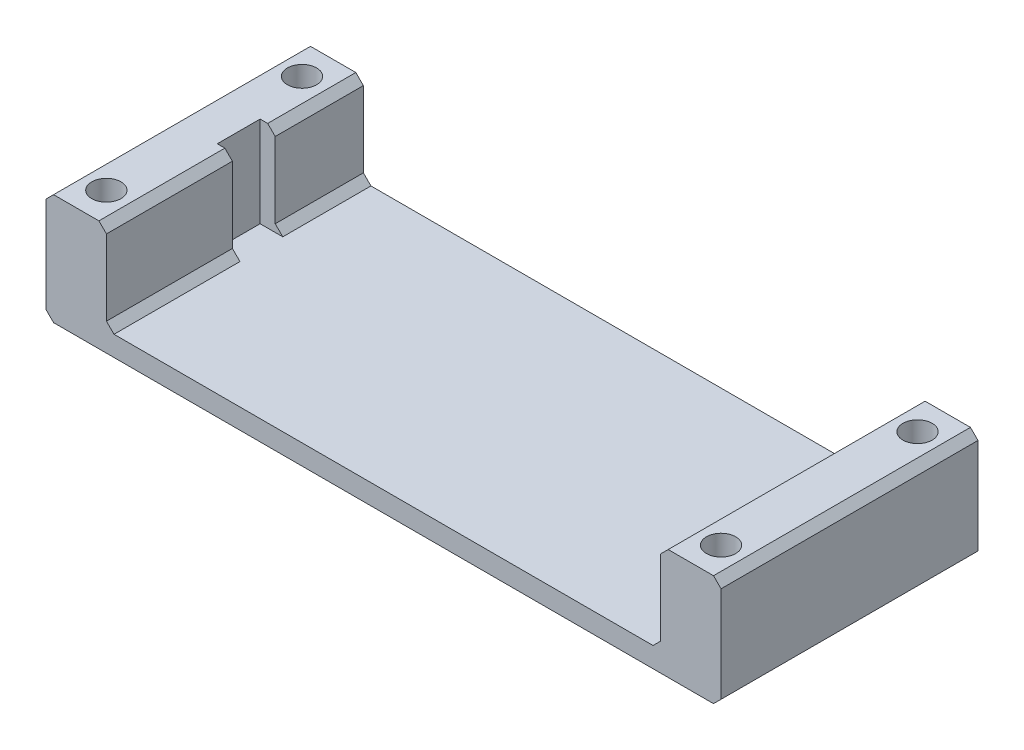
SolidWorks part; units mm, degrees
ref_plane "Front Plane" through (0, 0, 0) normal (0, 0, 1) x (1, 0, 0)
ref_plane "Top Plane" through (0, 0, 0) normal (0, 1, 0) x (1, 0, 0)
ref_plane "Right Plane" through (0, 0, 0) normal (1, 0, 0) x (0, 0, -1)
sketch "Sketch1" plane through (0, 0, 0) normal (0, 1, 0) x (1, 0, 0)
  line L1 (0, 0) -> (67, 0)
  line L2 (0, 0) -> (0, 25.5)
  line L3 (0, 25.5) -> (67, 25.5)
  line L4 (67, 0) -> (67, 25.5)
  dimension "D1" = 67
  dimension "D2" = 25.5
extrude "Boss-Extrude1" add sketch "Sketch1" along normal blind 2
sketch "Sketch3" plane through (0, 2, 0) normal (0, 1, 0) x (1, 0, 0)
  line L0 (0, 0) -> (67, 0) construction
  line L1 (67, 25.5) -> (61, 25.5)
  line L2 (67, 25.5) -> (67, 0)
  line L3 (67, 0) -> (61, 0)
  line L4 (61, 25.5) -> (61, 0)
  dimension "D1" = 6
extrude "Boss-Extrude2" add sketch "Sketch3" along normal blind 9
sketch "Sketch4" plane through (0, 2, 0) normal (0, 1, 0) x (1, 0, 0)
  line L0 (61, 25.5) -> (0, 25.5) construction
  line L1 (0, 0) -> (6, 0)
  line L2 (0, 0) -> (0, 25.5)
  line L3 (0, 25.5) -> (6, 25.5)
  line L4 (6, 0) -> (6, 12.5)
  line L5 (6, 16.75) -> (6, 25.5)
  line L6 (6, 16.75) -> (4.5, 16.75)
  line L8 (6, 12.5) -> (4.5, 12.5)
  line L9 (4.5, 16.75) -> (4.5, 12.5)
  dimension "D1" = 6
  dimension "D2" = 1.5
  dimension "D3" = 12.5
  dimension "D4" = 4.25
extrude "Boss-Extrude3" add sketch "Sketch4" along normal blind 9
sketch "Sketch6" plane through (0, 11, 0) normal (0, 1, 0) x (1, 0, 0)
  line L0 (2.8997, 25.5) -> (3, 0) construction
  line L1 (6, 25.5) -> (0, 25.5) construction
  line L2 (0, 0) -> (6, 0) construction
  line L3 (64, 25.5) -> (64, 0) construction
  line L4 (67, 25.5) -> (61, 25.5) construction
  line L5 (61, 0) -> (67, 0) construction
  circle A0 centre (2.9115, 22.5) radius 1.45
  circle A1 centre (2.9882, 3) radius 1.45
  circle A2 centre (64, 22.5) radius 1.45
  circle A3 centre (64, 3) radius 1.45
  dimension "D1" = 2.9
  dimension "D2" = 2.9
  dimension "D3" = 3
  dimension "D5" = 2.9
  dimension "D6" = 2.9
  dimension "D4" = 3
extrude "Cut-Extrude1" cut sketch "Sketch6" against normal blind 3
chamfer "Chamfer1" distance 0.75 angle 45 10 edges at (6, 2, -21.125) (6, 2, -6.25) (61, 2, -12.75) (67, 11, -12.75) (0, 11, -12.75) (0, 0, -12.75) (67, 0, -12.75) (6, 11, -21.125) (6, 11, -6.25) (61, 11, -12.75)
sketch "Sketch7" plane through (0, 8, 0) normal (0, 1, 0) x (1, 0, 0)
  circle A0 centre (2.9115, 22.5) radius 1.05
  circle A1 centre (2.9882, 3) radius 1.05
  circle A2 centre (64, 3) radius 1.05
  circle A3 centre (64, 22.5) radius 1.05
  dimension "D1" = 2.1
  dimension "D2" = 2.1
  dimension "D3" = 2.1
  dimension "D4" = 2.1
extrude "Cut-Extrude2" cut sketch "Sketch7" against normal blind 3
